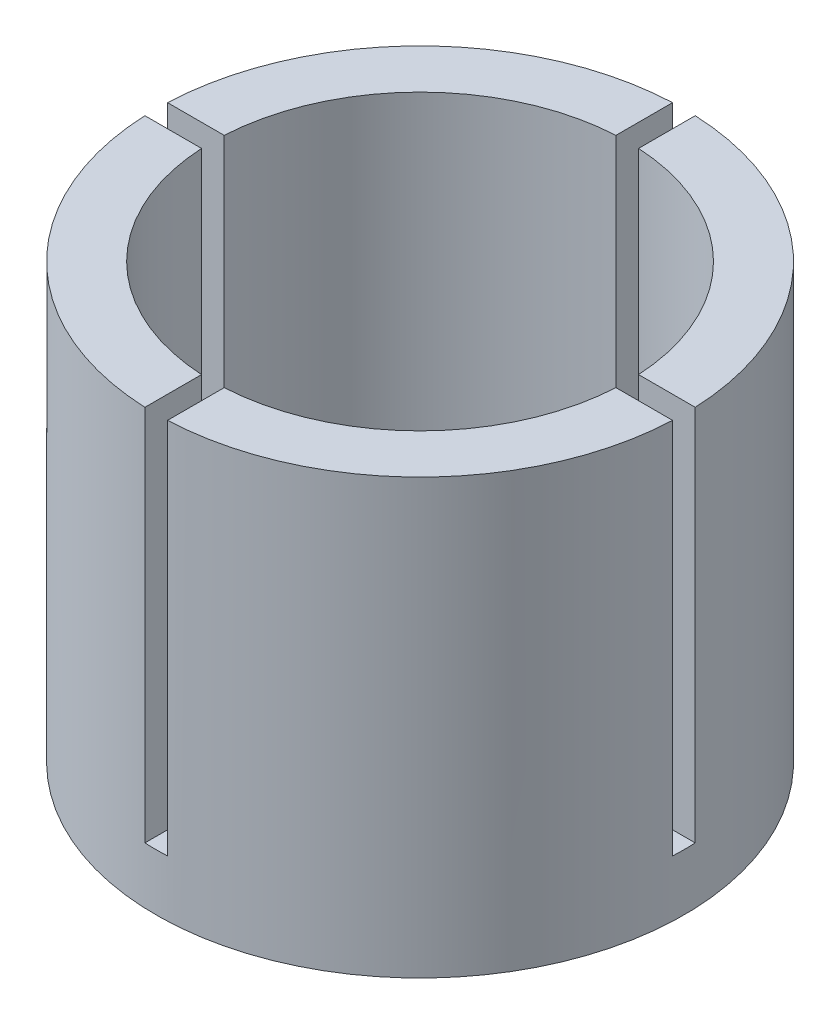
SolidWorks part; units mm, degrees
ref_plane "Front Plane" through (0, 0, 0) normal (0, 0, 1) x (1, 0, 0)
ref_plane "Top Plane" through (0, 0, 0) normal (0, 1, 0) x (1, 0, 0)
ref_plane "Right Plane" through (0, 0, 0) normal (1, 0, 0) x (0, 0, -1)
sketch "Sketch2" plane through (0, 0, 0) normal (0, 0, 1) x (1, 0, 0)
  line L0 (0, 0) -> (14, 0)
  line L1 (14, 0) -> (14, 23)
  line L2 (14, 23) -> (11, 23)
  line L3 (11, 23) -> (11, 3)
  line L5 (0, 8) -> (0, 0)
  line L6 (11, 3) -> (7.5, 3)
  line L7 (7.5, 3) -> (7.5, 8)
  line L8 (7.5, 8) -> (0, 8)
  point P6 (0, 0)
  point P10 (0, 7.2512)
  point P11 (16.0913, 1.4035)
  dimension "D1" = 11
  dimension "D2" = 3
  dimension "D3" = 3
  dimension "D4" = 20
  dimension "D5" = 5
  dimension "D6" = 7.5
revolve "Revolve1" add sketch "Sketch2" angle 360 about L5
sketch "Sketch3" plane through (0, 23, 0) normal (0, 1, 0) x (1, 0, 0)
  line L1 (-0.6, -14) -> (0.6, -14)
  line L2 (-0.6, -14) -> (-0.6, 14)
  line L3 (-0.6, 14) -> (0.6, 14)
  line L4 (0.6, -14) -> (0.6, 14)
  line L5 (-0.6, -14) -> (0.6, 14) construction
  line L6 (-0.6, 14) -> (0.6, -14) construction
  line L7 (-14, -0.6) -> (14, -0.6)
  line L8 (-14, -0.6) -> (-14, 0.6)
  line L9 (-14, 0.6) -> (14, 0.6)
  line L10 (14, -0.6) -> (14, 0.6)
  line L11 (-14, -0.6) -> (14, 0.6) construction
  line L12 (-14, 0.6) -> (14, -0.6) construction
  circle A0 centre (0, 0) radius 14 construction
  point P0 (0, 0)
  point P6 (0, 0)
  circle M9 centre (0, 0) radius 11
  circle M10 centre (0, 0) radius 14
  dimension "D1" = 1.2
extrude "Cut-Extrude1" cut sketch "Sketch3" against normal up to surface (20 mm away) contours L4 L2 M10 M9 | L9 L7 M9 M10 | L4 L2 M9 M10 | L9 L7 M10 M9 up to face at (-7.5, 3, 0)
